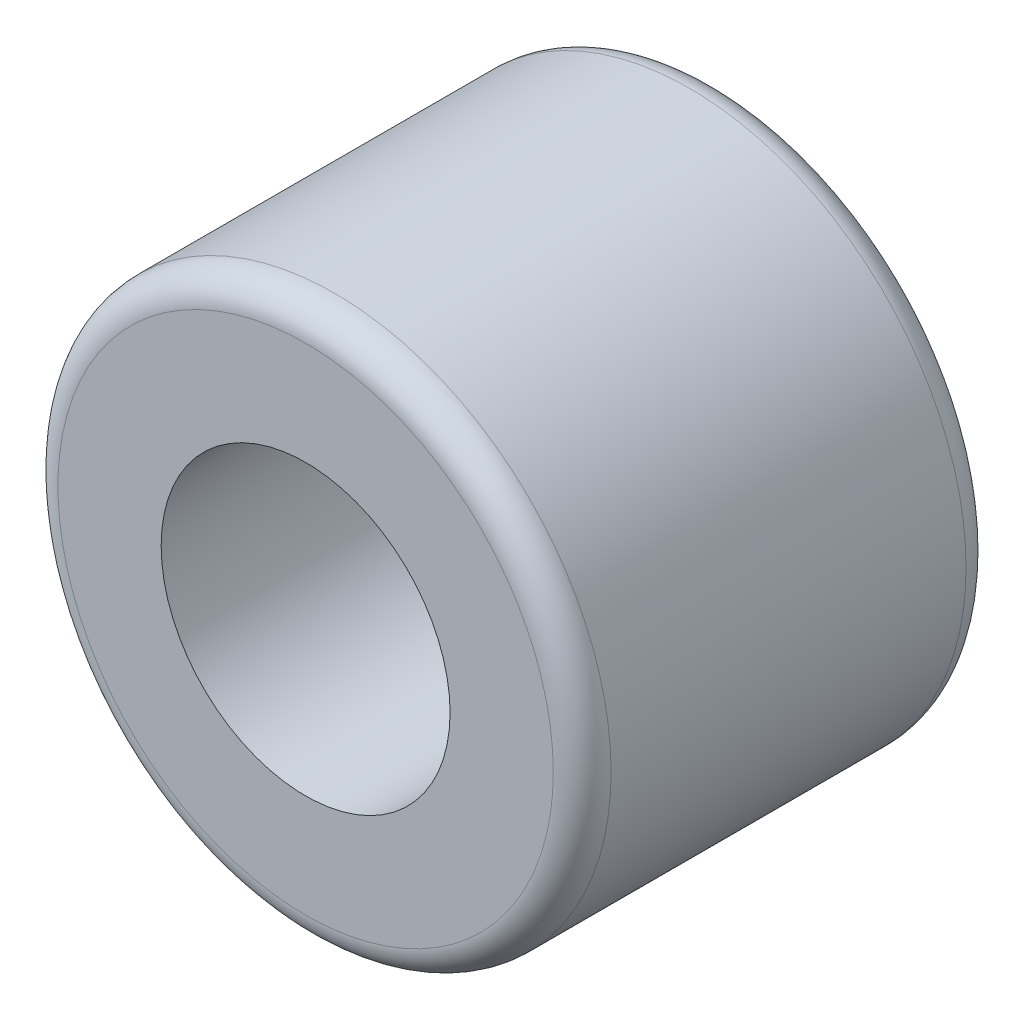
SolidWorks part; units mm, degrees
ref_plane "Front Plane" through (0, 0, 0) normal (0, 0, 1) x (1, 0, 0)
ref_plane "Top Plane" through (0, 0, 0) normal (0, 1, 0) x (1, 0, 0)
ref_plane "Right Plane" through (0, 0, 0) normal (1, 0, 0) x (0, 0, -1)
sketch "Sketch1" plane through (0, 0, 0) normal (0, 0, 1) x (1, 0, 0)
  circle A0 centre (0, 0) radius 8.509
  circle A1 centre (0, 0) radius 4.445
  dimension "D1" = 17.018
  dimension "D2" = 8.89
extrude "Boss-Extrude1" add sketch "Sketch1" along normal blind 12.7
fillet "Fillet1" radius 0.889 2 edges at (8.509, 0, 0) (8.509, 0, 12.7)
